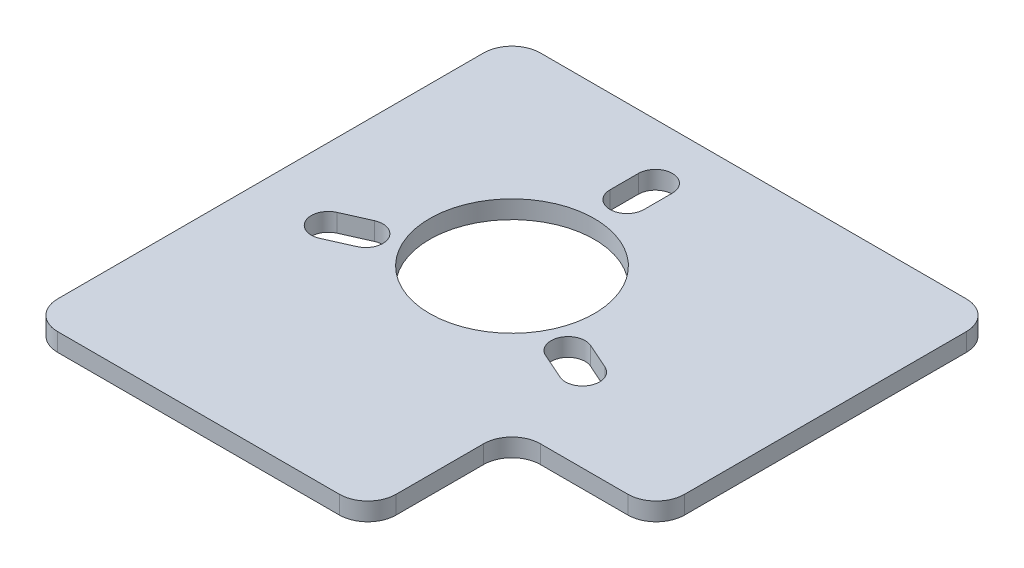
SolidWorks part; units mm, degrees
ref_plane "Front Plane" through (0, 0, 0) normal (0, 0, 1) x (1, 0, 0)
ref_plane "Top Plane" through (0, 0, 0) normal (0, 1, 0) x (1, 0, 0)
ref_plane "Right Plane" through (0, 0, 0) normal (1, 0, 0) x (0, 0, -1)
sketch "Sketch1" plane through (0, 0, 0) normal (0, 1, 0) x (1, 0, 0)
  line L1 (0, 0) -> (170, 0)
  line L2 (0, 0) -> (0, 170)
  line L3 (0, 170) -> (170, 170)
  line L4 (170, 0) -> (170, 170)
  circle A0 centre (70, 100) radius 29
  dimension "D3" = 58
  dimension "D4" = 70
  dimension "D5" = 70
  dimension "D1" = 170
  dimension "D2" = 170
extrude "Boss-Extrude1" add sketch "Sketch1" along normal blind 6.35
sketch "Sketch2" plane through (0, 6.35, 0) normal (0, 1, 0) x (1, 0, 0)
  line L1 (119.2, 0) -> (170, 0)
  line L2 (119.2, 0) -> (119.2, 50.8)
  line L3 (119.2, 50.8) -> (170, 50.8)
  line L4 (170, 0) -> (170, 50.8)
  dimension "D1" = 50.8
  dimension "D2" = 50.8
extrude "Cut-Extrude1" cut sketch "Sketch2" against normal through all
fillet "Fillet1" radius 10 6 edges at (170, 3.175, -170) (0, 3.175, -170) (119.2, 3.175, -50.8) (119.2, 3.175, 0) (170, 3.175, -50.8) (0, 3.175, 0)
sketch "Sketch3" plane through (0, 6.35, 0) normal (0, 1, 0) x (1, 0, 0)
  line L0 (70, 100) -> (25.2363, 80.0699) construction
  line L1 (70, 100) -> (114.7637, 80.0699) construction
  line L2 (70, 100) -> (70, 150.5) construction
  line L3 (70, 100) -> (139.8398, 100) construction
  line L4 (25.2363, 80.0699) -> (34.3717, 84.1373) construction
  line L5 (22.7959, 85.5512) -> (31.9313, 89.6185)
  line L6 (27.6767, 74.5886) -> (36.8121, 78.656)
  line L7 (114.7637, 80.0699) -> (105.6283, 84.1373) construction
  line L8 (112.3233, 74.5886) -> (103.1879, 78.656)
  line L9 (117.2041, 85.5512) -> (108.0687, 89.6185)
  line L10 (70, 150.5) -> (70, 140.5) construction
  line L11 (76, 150.5) -> (76, 140.5)
  line L12 (64, 150.5) -> (64, 140.5)
  arc A0 (22.7959, 85.5512) -> (27.6767, 74.5886) centre (25.2363, 80.0699) ccw
  arc A1 (36.8121, 78.656) -> (31.9313, 89.6185) centre (34.3717, 84.1373) ccw
  arc A2 (112.3233, 74.5886) -> (117.2041, 85.5512) centre (114.7637, 80.0699) ccw
  arc A3 (108.0687, 89.6185) -> (103.1879, 78.656) centre (105.6283, 84.1373) ccw
  arc A4 (76, 150.5) -> (64, 150.5) centre (70, 150.5) ccw
  arc A5 (64, 140.5) -> (76, 140.5) centre (70, 140.5) ccw
  point P3 (29.804, 82.1036)
  point P12 (110.196, 82.1036)
  point P18 (70, 145.5)
  dimension "D4" = 6
  dimension "D1" = 50.5
  dimension "D2" = 24
  dimension "D3" = 24
  dimension "D5" = 10
  dimension "D6" = 49
extrude "Cut-Extrude2" cut sketch "Sketch3" against normal through all
